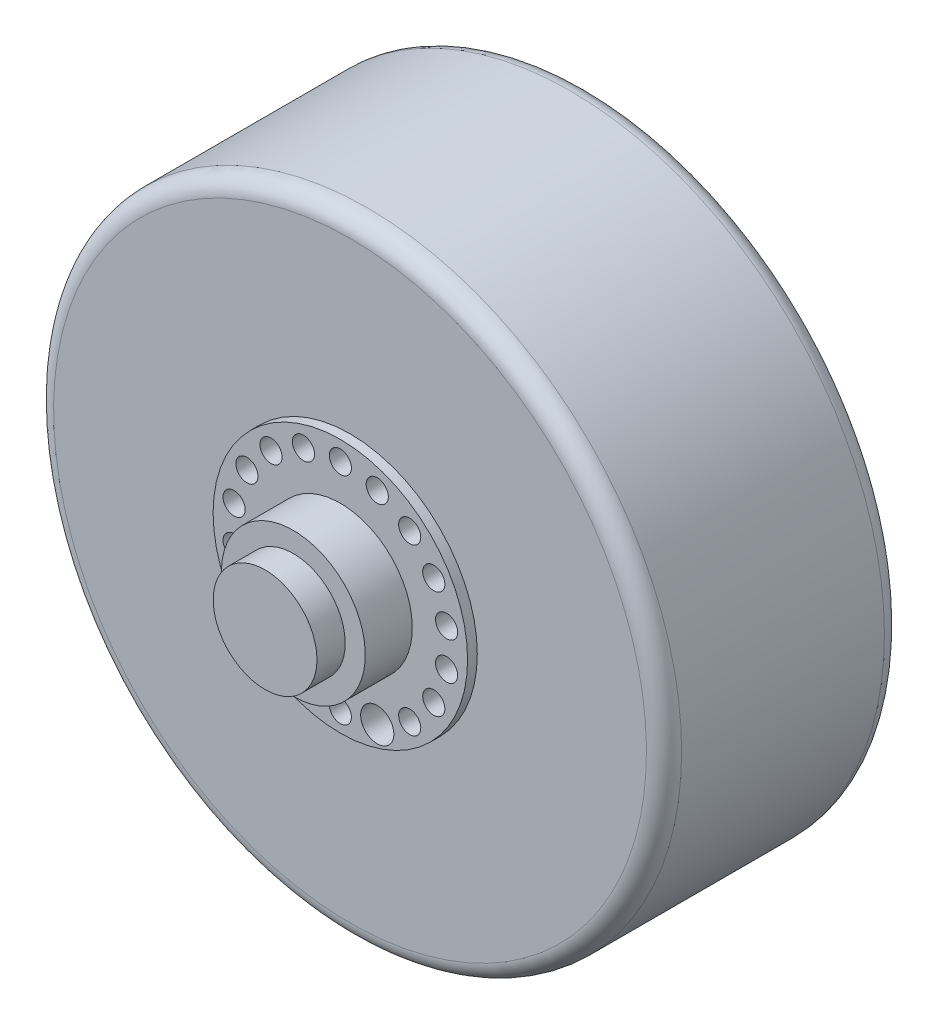
SolidWorks part; units mm, degrees
material "Cast Carbon Steel"
ref_plane "X-Y Datum" through (0, 0, 0) normal (0, 0, 1) x (1, 0, 0)
ref_plane "X-Z Datum" through (0, 0, 0) normal (0, 1, 0) x (1, 0, 0)
ref_plane "Y-Z Datum" through (0, 0, 0) normal (1, 0, 0) x (0, 0, -1)
sketch "Sketch1" plane through (0, 0, 0) normal (1, 0, 0) x (0, 0, -1)
  line L0 (-87.2363, 0) -> (87.2363, 0)
  line L1 (-87.2363, 18.7452) -> (-87.2363, -18.7452)
  line L2 (-87.2363, 18.7452) -> (-77.0255, 18.7452)
  line L3 (-77.0255, 18.7452) -> (-77.0255, -18.7452)
  line L4 (-87.2363, -18.7452) -> (-77.0255, -18.7452)
  line L5 (-77.0255, 26.0096) -> (-77.0255, -26.0096)
  line L6 (-60.0329, 26.0096) -> (-60.0329, -26.0096)
  line L7 (-77.0255, 26.0096) -> (-60.0329, 26.0096)
  line L8 (-77.0255, -26.0096) -> (-60.0329, -26.0096)
  line L9 (-60.0329, 45.9994) -> (-60.0329, -45.9994)
  line L10 (-56.5277, 45.9994) -> (-56.5277, -45.9994)
  line L11 (-60.0329, 45.9994) -> (-56.5277, 45.9994)
  line L12 (-60.0329, -45.9994) -> (-56.5277, -45.9994)
  line L13 (-56.5277, 113.5126) -> (-56.5277, -113.5126)
  line L14 (29.4767, 113.5126) -> (29.4767, -113.5126)
  line L15 (-56.5277, 113.5126) -> (29.4767, 113.5126)
  line L16 (-56.5277, -113.5126) -> (29.4767, -113.5126)
  line L17 (29.4767, 46.99) -> (29.4767, -46.99)
  line L18 (35.8267, 46.99) -> (35.8267, -46.99)
  line L19 (29.4767, -46.99) -> (35.8267, -46.99)
  line L20 (29.4767, 46.99) -> (35.8267, 46.99)
  line L21 (72.7329, 15.113) -> (72.7329, -15.113)
  line L22 (72.7329, -15.113) -> (60.6933, -15.113)
  line L23 (72.7329, 15.113) -> (60.6933, 15.113)
  line L24 (72.7329, 10.033) -> (72.7329, -10.033)
  line L25 (87.2363, 10.033) -> (87.2363, -10.033)
  line L26 (72.7329, 10.033) -> (87.2363, 10.033)
  line L27 (72.7329, -10.033) -> (87.2363, -10.033)
  line L28 (53.4797, 27.5082) -> (53.4797, -27.5082)
  line L29 (60.6933, 27.5082) -> (60.6933, -27.5082)
  line L30 (53.4797, 27.5082) -> (60.6933, 27.5082)
  line L31 (53.4797, -27.5082) -> (60.6933, -27.5082)
  line L32 (53.4797, 15.113) -> (35.8267, 15.113)
  line L33 (53.4797, -15.113) -> (35.8267, -15.113)
  point P4 (0, 0)
  point P8 (-87.2363, 0)
  point P11 (-77.0255, 0)
  point P14 (-77.0255, 0)
  point P17 (-60.0329, 0)
  point P20 (-60.0329, 0)
  point P23 (-56.5277, 0)
  point P26 (-56.5277, 0)
  point P29 (29.4767, 0)
  point P32 (29.4767, 0)
  point P35 (35.8267, 0)
  point P38 (72.7329, 0)
  point P42 (72.7329, 0)
  point P45 (87.2363, 0)
  point P48 (53.4797, 0)
  point P51 (60.6933, 0)
  dimension "D1" = 174.4726
  dimension "D2" = 113.5126
  dimension "D3" = 18.7452
  dimension "D4" = 26.0096
  dimension "D5" = 10.2108
  dimension "D6" = 16.9926
  dimension "D7" = 45.9994
  dimension "D8" = 3.5052
  dimension "D9" = 86.0044
  dimension "D10" = 46.99
  dimension "D11" = 6.35
  dimension "D12" = 17.653
  dimension "D13" = 30.226
  dimension "D14" = 55.0164
  dimension "D15" = 20.066
  dimension "D16" = 7.2136
  dimension "D17" = 14.5034
revolve "Revolve1" add sketch "Sketch1" angle 360 about L0
sketch "Sketch2" plane through (0, 0, 60.0329) normal (0, 0, 1) x (1, 0, 0)
  circle A0 centre (0, 0) radius 39 construction
  circle A1 centre (0, 39) radius 4
  point P3 (0, 39)
  point P9 (13.3388, 36.648)
  point P10 (25.0687, 29.8757)
  point P11 (33.775, 19.5)
  point P12 (38.4075, 6.7723)
  point P13 (38.4075, -6.7723)
  point P14 (33.775, -19.5)
  point P15 (25.0687, -29.8757)
  point P16 (13.3388, -36.648)
  point P17 (0, -39)
  point P18 (-13.3388, -36.648)
  point P19 (-25.0687, -29.8757)
  point P20 (-33.775, -19.5)
  point P21 (-38.4075, -6.7723)
  point P22 (-38.4075, 6.7723)
  point P23 (-33.775, 19.5)
  point P24 (-25.0687, 29.8757)
  point P25 (-13.3388, 36.648)
  point P26 (0, 0)
  dimension "D1" = 78
  dimension "D2" = 8
  dimension "D3" = 18
extrude "Cut-Extrude1" cut sketch "Sketch2" against normal blind 9.525
pattern_circular "CirPattern1" count 18 over 360 about axis through (0, 0, 0) along (0, 0, 1) skipping 8, 10 of "Cut-Extrude1"
sketch "Sketch4" plane through (0, 0, 60.0329) normal (0, 0, 1) x (1, 0, 0)
  circle A0 centre (-13.3388, -36.648) radius 6
  circle A1 centre (13.3388, -36.648) radius 6
  dimension "D1" = 12
extrude "Cut-Extrude2" cut sketch "Sketch4" against normal blind 9.525
fillet "Fillet1" radius 6.35 2 edges at (0, -113.5126, 56.5277) (0, -113.5126, -29.4767)
sketch "Sketch5" plane through (0, 0, -29.4767) normal (0, 0, -1) x (-1, 0, 0)
  circle A0 centre (0, 0) radius 37.5 construction
  circle A1 centre (0, 37.5) radius 4
  circle A2 centre (32.476, 18.75) radius 4
  circle A3 centre (32.476, -18.75) radius 4
  circle A4 centre (0, -37.5) radius 4
  circle A5 centre (-32.476, -18.75) radius 4
  circle A6 centre (-32.476, 18.75) radius 4
  circle A7 centre (0, 0) radius 24.5
  circle A8 centre (0, 0) radius 27.94
  point P3 (0, 37.5)
  point P19 (0, 0)
  dimension "D1" = 75
  dimension "D2" = 6
  dimension "D3" = 8
  dimension "D4" = 49
  dimension "D5" = 55.88
extrude "Cut-Extrude3" cut sketch "Sketch5" against normal blind 9.525
